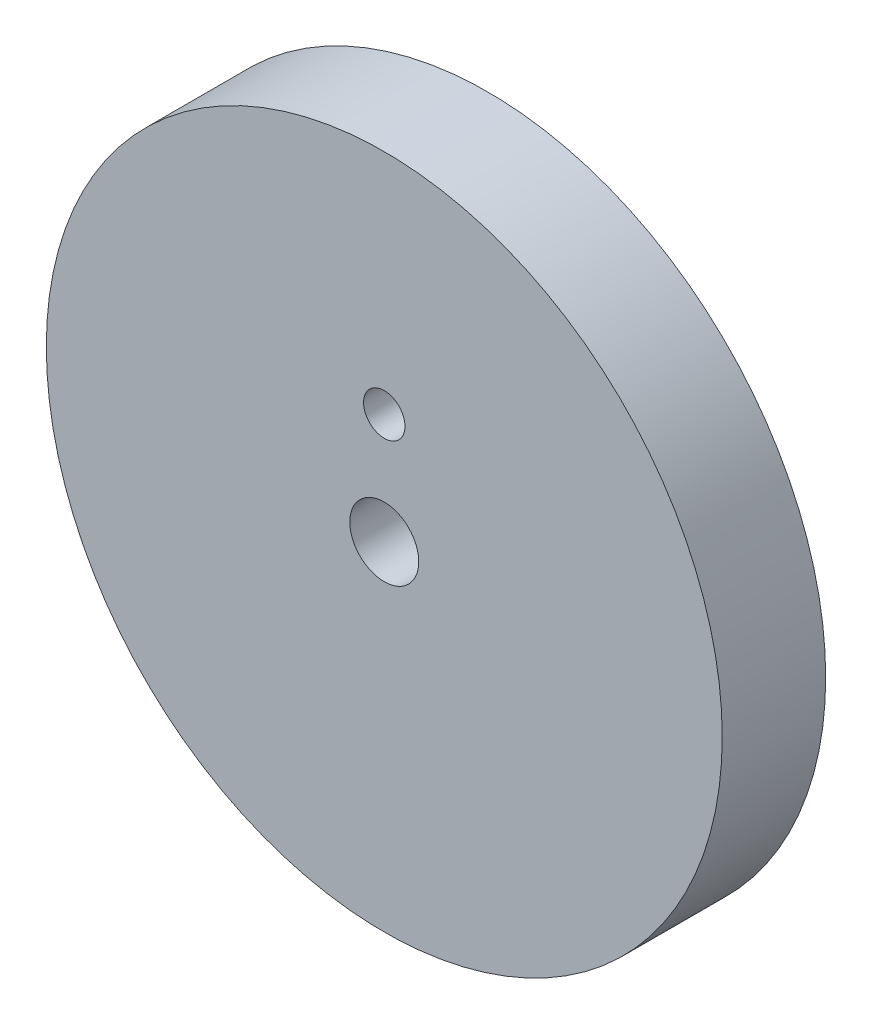
SolidWorks part; units mm, degrees
ref_plane "Plan de face" through (0, 0, 0) normal (0, 0, 1) x (1, 0, 0)
ref_plane "Plan de dessus" through (0, 0, 0) normal (0, 1, 0) x (1, 0, 0)
ref_plane "Plan de droite" through (0, 0, 0) normal (1, 0, 0) x (0, 0, -1)
sketch "Esquisse1" plane through (0, 0, 0) normal (0, 0, 1) x (1, 0, 0)
  circle A0 centre (0, 0) radius 49
  dimension "D1" = 98
extrude "Boss.-Extru.1" add sketch "Esquisse1" along normal blind 15
sketch "Esquisse2" plane through (0, 0, 0) normal (0, 0, -1) x (-1, 0, 0)
  line L0 (0, 0) -> (0, 32.7973) construction
  circle A0 centre (0, 0) radius 5
  circle A1 centre (0, 16) radius 3
  dimension "D1" = 10
  dimension "D2" = 6
  dimension "D3" = 16
extrude "Enlèv. mat.-Extru.1" cut sketch "Esquisse2" against normal through all
